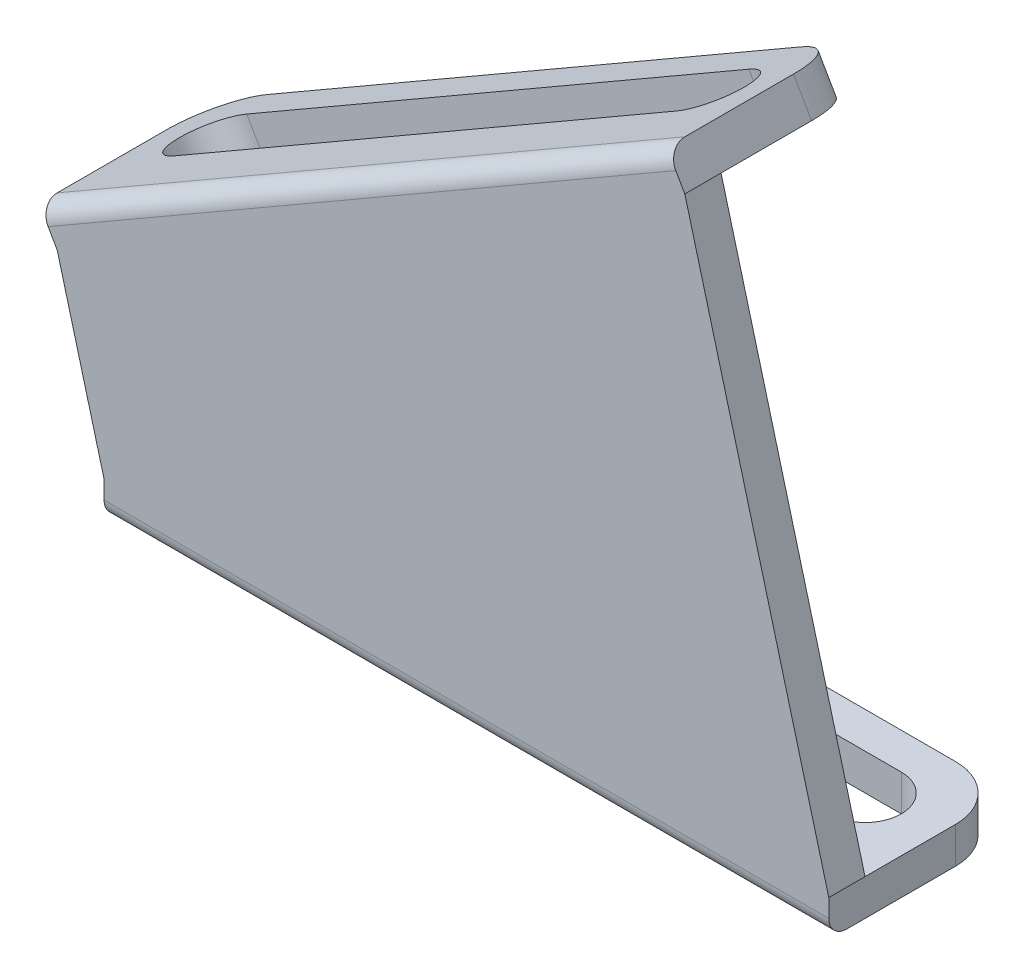
SolidWorks part; units mm, degrees
ref_plane "Front Plane" through (0, 0, 0) normal (0, 0, 1) x (1, 0, 0)
ref_plane "Top Plane" through (0, 0, 0) normal (0, 1, 0) x (1, 0, 0)
ref_plane "Right Plane" through (0, 0, 0) normal (1, 0, 0) x (0, 0, -1)
sketch "Sketch1" plane through (0, 0, 0) normal (0, 1, 0) x (1, 0, 0)
  line L0 (4, 8) -> (36, 8)
  line L1 (0, 0) -> (40, 0)
  line L2 (0, 0) -> (0, 7)
  line L3 (3, 10) -> (37, 10)
  line L4 (40, 0) -> (40, 7)
  line L5 (36, 4) -> (4, 4)
  arc A0 (0, 7) -> (3, 10) centre (3, 7) cw
  arc A1 (37, 10) -> (40, 7) centre (37, 7) cw
  arc A2 (4, 8) -> (4, 4) centre (4, 6) ccw
  arc A3 (36, 4) -> (36, 8) centre (36, 6) ccw
  point P10 (0, 10)
  point P13 (40, 10)
  dimension "D3" = 3
  dimension "D4" = 3
  dimension "D7" = 4
  dimension "D8" = 4
  dimension "D1" = 10
  dimension "D2" = 40
  dimension "D5" = 0
  dimension "D6" = 4
  dimension "D9" = 4
  dimension "D10" = 4
  dimension "D11" = 32
  dimension "D12" = 32
extrude "Boss-Extrude2" add sketch "Sketch1" along normal blind 2
sketch "Sketch2" plane through (0, 0, 0) normal (0, 0, 1) x (1, 0, 0)
  line L0 (0, 2) -> (-2.5882, 11.6593)
  line L1 (-2.5882, 11.6593) -> (32.0528, 31.6593)
  line L2 (32.0528, 31.6593) -> (40, 2)
  line L3 (0, 2) -> (40, 2)
  dimension "D1" = 30
  dimension "D2" = 105
  dimension "D3" = 75
  dimension "D4" = 10
extrude "Boss-Extrude3" add sketch "Sketch2" against normal blind 2
sketch "Sketch3" plane through (-5.6957, 9.8652, 0) normal (-0.5, 0.866, 0) x (0.866, 0.5, 0)
  line L0 (7.5882, 4) -> (39.5882, 4)
  line L1 (3.5882, 0) -> (43.5882, 0)
  line L2 (3.5882, 0) -> (3.5882, 7)
  line L3 (6.5882, 10) -> (40.5882, 10)
  line L4 (43.5882, 0) -> (43.5882, 7)
  line L6 (39.5882, 8) -> (7.5882, 8)
  arc A0 (3.5882, 7) -> (6.5882, 10) centre (6.5882, 7) cw
  arc A1 (40.5882, 10) -> (43.5882, 7) centre (40.5882, 7) cw
  arc A2 (7.5882, 8) -> (7.5882, 4) centre (7.5882, 6) ccw
  arc A3 (39.5882, 4) -> (39.5882, 8) centre (39.5882, 6) ccw
  point P7 (3.5882, 10)
  dimension "D2" = 3
  dimension "D3" = 3
  dimension "D9" = 4
  dimension "D10" = 4
  dimension "D1" = 10
  dimension "D4" = 40
  dimension "D5" = 0
  dimension "D6" = 4
  dimension "D7" = 4
  dimension "D8" = 4
extrude "Boss-Extrude4" add sketch "Sketch3" along normal blind 2
fillet "Fillet1" radius 1 1 edges at (20, 0, 0)
fillet "Fillet2" radius 1 1 edges at (13.7323, 23.3913, 0)
